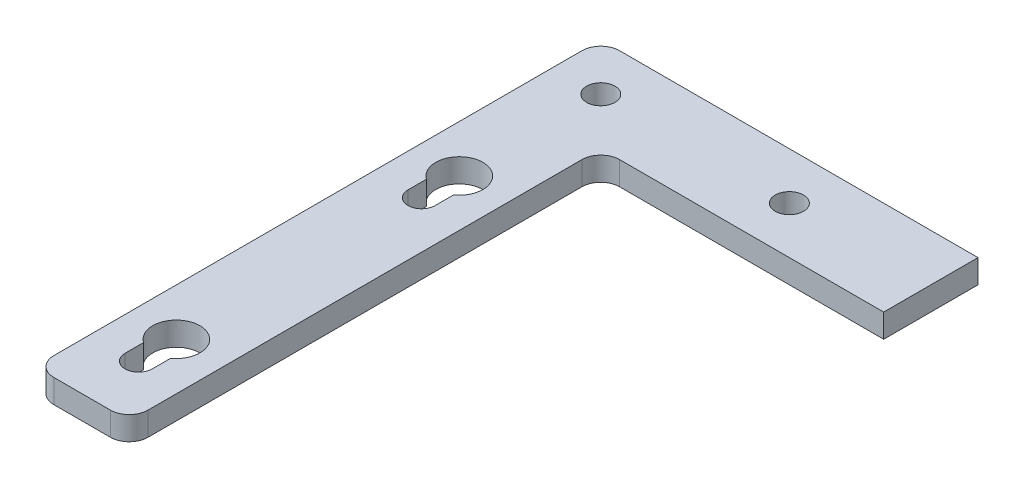
SolidWorks part; units mm, degrees
ref_plane "Front Plane" through (0, 0, 0) normal (0, 0, 1) x (1, 0, 0)
ref_plane "Top Plane" through (0, 0, 0) normal (0, 1, 0) x (1, 0, 0)
ref_plane "Right Plane" through (0, 0, 0) normal (1, 0, 0) x (0, 0, -1)
sketch "Sketch1" plane through (0, 0, 0) normal (0, 1, 0) x (1, 0, 0)
  line L0 (6.35, 76.2) -> (6.35, 0) construction
  line L1 (0, 0) -> (12.7, 0)
  line L2 (0, 0) -> (0, 76.2)
  line L3 (0, 76.2) -> (12.7, 76.2)
  line L4 (12.7, 0) -> (12.7, 76.2)
  line L5 (12.7, 76.2) -> (50.8, 76.2)
  line L6 (12.7, 76.2) -> (12.7, 63.5)
  line L7 (12.7, 63.5) -> (50.8, 63.5)
  line L8 (50.8, 76.2) -> (50.8, 63.5)
  line L9 (50.8, 63.5) -> (44.45, 63.5)
  dimension "D1" = 76.2
  dimension "D2" = 12.7
  dimension "D3" = 38.1
  dimension "D4" = 12.7
extrude "Boss-Extrude1" add sketch "Sketch1" along normal blind 3.175
sketch "Sketch2" plane through (0, 3.175, 0) normal (0, 1, 0) x (1, 0, 0)
  line L0 (6.35, 76.2) -> (6.35, 0) construction
  line L1 (0, 76.2) -> (50.8, 76.2) construction
  line L2 (0, 0) -> (12.7, 0) construction
  line L3 (4.5212, 45.72) -> (4.5212, 48.2046)
  line L4 (8.1788, 45.72) -> (8.1788, 48.2046)
  line L5 (4.5212, 7.62) -> (4.5212, 10.1046)
  line L6 (8.1788, 7.62) -> (8.1788, 10.1046)
  line L7 (50.8, 69.85) -> (0, 69.85) construction
  line L8 (50.8, 76.2) -> (50.8, 63.5) construction
  line L9 (0, 0) -> (0, 76.2) construction
  circle A0 centre (6.35, 50.8) radius 3.175
  circle A1 centre (6.35, 12.7) radius 3.175
  circle A2 centre (6.35, 7.62) radius 1.8288
  circle A3 centre (6.35, 45.72) radius 1.8288
  circle A4 centre (31.75, 69.85) radius 1.905
  circle A5 centre (6.35, 69.85) radius 1.905
  dimension "D1" = 6.35
  dimension "D3" = 3.6576
  dimension "D7" = 3.81
  dimension "D2" = 38.1
  dimension "D4" = 5.08
  dimension "D5" = 5.08
  dimension "D6" = 12.7
  dimension "D8" = 25.4
  dimension "D9" = 6.35
extrude "Cut-Extrude1" cut sketch "Sketch2" against normal blind 3.175
fillet "Fillet3" radius 2.54 4 edges at (12.7, 1.5875, -63.5) (12.7, 1.5875, 0) (0, 1.5875, 0) (0, 1.5875, -76.2)
